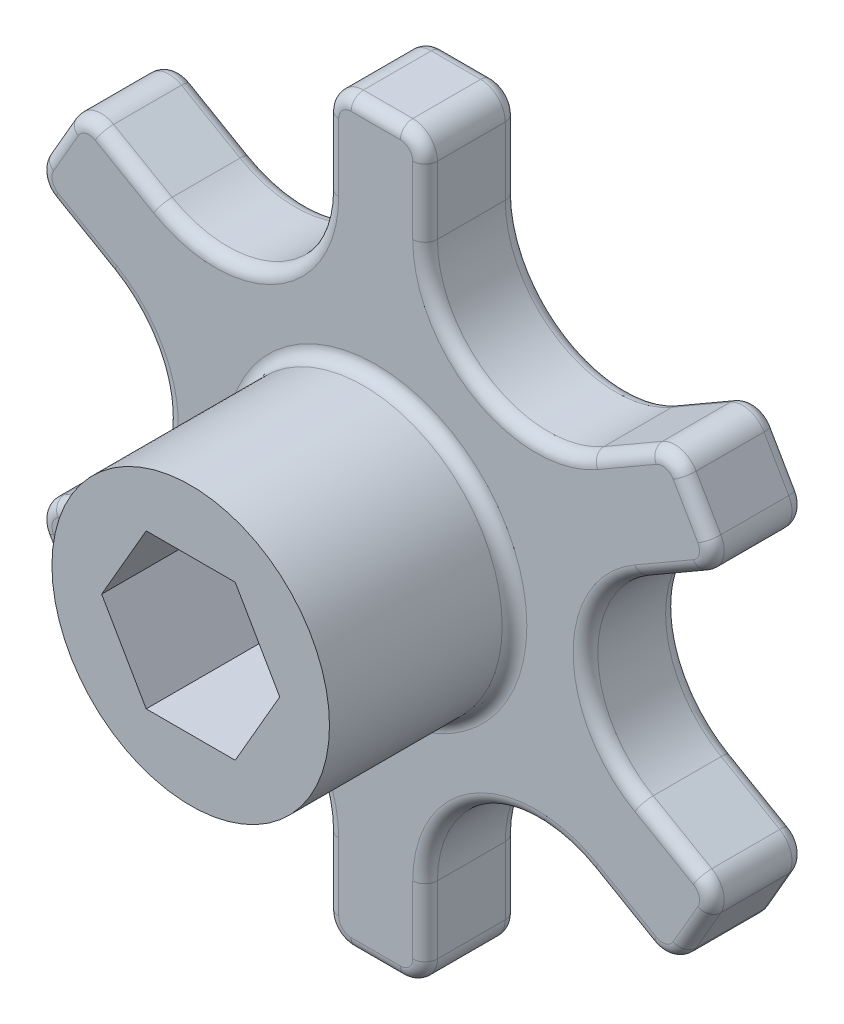
SolidWorks part; units mm, degrees
ref_plane "Front Plane" through (0, 0, 0) normal (0, 0, 1) x (1, 0, 0)
ref_plane "Top Plane" through (0, 0, 0) normal (0, 1, 0) x (1, 0, 0)
ref_plane "Right Plane" through (0, 0, 0) normal (1, 0, 0) x (0, 0, -1)
sketch "Sketch1" plane through (0, 0, 0) normal (0, 0, 1) x (1, 0, 0)
  line L0 (-5.08, 35.56) -> (-5.08, 28.5962)
  line L1 (-2.54, 38.1) -> (2.54, 38.1)
  line L2 (5.08, 35.56) -> (5.08, 28.5962)
  line L3 (55, 0) -> (-55, 0) construction
  line L5 (0, -55) -> (0, 55) construction
  line L6 (33.3359, 13.3806) -> (27.305, 9.8987)
  line L7 (28.2559, 22.1794) -> (22.225, 18.6975)
  line L8 (31.7256, 21.2497) -> (34.2656, 16.8503)
  line L9 (28.2559, -22.1794) -> (22.225, -18.6975)
  line L10 (33.3359, -13.3806) -> (27.305, -9.8987)
  line L11 (34.2656, -16.8503) -> (31.7256, -21.2497)
  line L12 (-5.08, -35.56) -> (-5.08, -28.5962)
  line L13 (5.08, -35.56) -> (5.08, -28.5962)
  line L14 (2.54, -38.1) -> (-2.54, -38.1)
  line L15 (-33.3359, -13.3806) -> (-27.305, -9.8987)
  line L16 (-28.2559, -22.1794) -> (-22.225, -18.6975)
  line L17 (-31.7256, -21.2497) -> (-34.2656, -16.8503)
  line L18 (-28.2559, 22.1794) -> (-22.225, 18.6975)
  line L19 (-33.3359, 13.3806) -> (-27.305, 9.8987)
  line L20 (-34.2656, 16.8503) -> (-31.7256, 21.2497)
  arc A0 (2.54, 38.1) -> (5.08, 35.56) centre (2.54, 35.56) cw
  arc A1 (-5.08, 35.56) -> (-2.54, 38.1) centre (-2.54, 35.56) cw
  arc A2 (34.2656, 16.8503) -> (33.3359, 13.3806) centre (32.0659, 15.5803) cw
  arc A3 (28.2559, 22.1794) -> (31.7256, 21.2497) centre (29.5259, 19.9797) cw
  arc A4 (31.7256, -21.2497) -> (28.2559, -22.1794) centre (29.5259, -19.9797) cw
  arc A5 (33.3359, -13.3806) -> (34.2656, -16.8503) centre (32.0659, -15.5803) cw
  arc A6 (-2.54, -38.1) -> (-5.08, -35.56) centre (-2.54, -35.56) cw
  arc A7 (5.08, -35.56) -> (2.54, -38.1) centre (2.54, -35.56) cw
  arc A8 (-34.2656, -16.8503) -> (-33.3359, -13.3806) centre (-32.0659, -15.5803) cw
  arc A9 (-28.2559, -22.1794) -> (-31.7256, -21.2497) centre (-29.5259, -19.9797) cw
  arc A10 (-31.7256, 21.2497) -> (-28.2559, 22.1794) centre (-29.5259, 19.9797) cw
  arc A11 (-33.3359, 13.3806) -> (-34.2656, 16.8503) centre (-32.0659, 15.5803) cw
  arc A12 (27.305, -9.8987) -> (27.305, 9.8987) centre (33.02, 0) cw
  arc A13 (22.225, 18.6975) -> (5.08, 28.5962) centre (16.51, 28.5962) cw
  arc A14 (5.08, -28.5962) -> (22.225, -18.6975) centre (16.51, -28.5962) cw
  arc A15 (-5.08, -28.5962) -> (-22.225, -18.6975) centre (-16.51, -28.5962) ccw
  arc A16 (-27.305, 9.8987) -> (-27.305, -9.8987) centre (-33.02, 0) cw
  arc A17 (-5.08, 28.5962) -> (-22.225, 18.6975) centre (-16.51, 28.5962) cw
  point P12 (5.08, 38.1)
  point P15 (-5.08, 38.1)
  point P56 (0, 0)
  dimension "D4" = 2.54
  dimension "D7" = 11.43
  dimension "D1" = 38.1
  dimension "D2" = 10.16
  dimension "D3" = 5.08
  dimension "D5" = 5.08
  dimension "D6" = 6
extrude "Boss-Extrude1" add sketch "Sketch1" along normal blind 9.525
sketch "Sketch2" plane through (0, 0, 9.525) normal (0, 0, 1) x (1, 0, 0)
  line L1 (9.1654, 0) -> (4.5827, 7.9375)
  line L2 (4.5827, 7.9375) -> (-4.5827, 7.9375)
  line L3 (-4.5827, 7.9375) -> (-9.1654, 0)
  line L4 (-9.1654, 0) -> (-4.5827, -7.9375)
  line L5 (-4.5827, -7.9375) -> (4.5827, -7.9375)
  line L6 (4.5827, -7.9375) -> (9.1654, 0)
  circle A0 centre (0, 0) radius 7.9375 construction
  circle A1 centre (0, 0) radius 14.2875
  dimension "D1" = 15.875
  dimension "D2" = 28.575
extrude "Boss-Extrude3" add sketch "Sketch2" along normal blind 19.05
fillet "Fillet3" radius 1.27 73 edges at (0, 38.1, 0) (-4.3361, 37.3561, 0) (-5.08, 32.0781, 0) (-10.795, 18.6975, 0) (-25.2404, 20.4384, 0) (-30.1833, 22.4332, 0) (-32.9956, 19.05, 0) (-34.5193, 14.9229, 0) (-30.3204, 11.6396, 0) (-21.59, 0, 0) (-30.3204, -11.6396, 0) (-34.5193, -14.9229, 0) (-32.9956, -19.05, 0) (-30.1833, -22.4332, 0) (-25.2404, -20.4384, 0) (-10.795, -18.6975, 0) (-5.08, -32.0781, 0) (-4.3361, -37.3561, 0) (0, -38.1, 0) (4.3361, -37.3561, 0) (5.08, -32.0781, 0) (10.795, -18.6975, 0) (25.2404, -20.4384, 0) (30.1833, -22.4332, 0) (32.9956, -19.05, 0) (34.5193, -14.9229, 0) (30.3204, -11.6396, 0) (21.59, 0, 0) (30.3204, 11.6396, 0) (34.5193, 14.9229, 0) (32.9956, 19.05, 0) (30.1833, 22.4332, 0) (25.2404, 20.4384, 0) (10.795, 18.6975, 0) (5.08, 32.0781, 0) (4.3361, 37.3561, 0) (-14.2875, 0, 9.525) (5.08, 32.0781, 9.525) (10.795, 18.6975, 9.525) (25.2404, 20.4384, 9.525) (30.1833, 22.4332, 9.525) (32.9956, 19.05, 9.525) (34.5193, 14.9229, 9.525) (30.3204, 11.6396, 9.525) (21.59, 0, 9.525) (30.3204, -11.6396, 9.525) (34.5193, -14.9229, 9.525) (32.9956, -19.05, 9.525) (30.1833, -22.4332, 9.525) (25.2404, -20.4384, 9.525) (10.795, -18.6975, 9.525) (5.08, -32.0781, 9.525) (4.3361, -37.3561, 9.525) (0, -38.1, 9.525) (-4.3361, -37.3561, 9.525) (-5.08, -32.0781, 9.525) (-10.795, -18.6975, 9.525) (-25.2404, -20.4384, 9.525) (-30.1833, -22.4332, 9.525) (-32.9956, -19.05, 9.525) (-34.5193, -14.9229, 9.525) (-30.3204, -11.6396, 9.525) (-21.59, 0, 9.525) (-30.3204, 11.6396, 9.525) (-34.5193, 14.9229, 9.525) (-32.9956, 19.05, 9.525) (-30.1833, 22.4332, 9.525) (-25.2404, 20.4384, 9.525) (-10.795, 18.6975, 9.525) (-5.08, 32.0781, 9.525) (-4.3361, 37.3561, 9.525) (0, 38.1, 9.525) (4.3361, 37.3561, 9.525)
